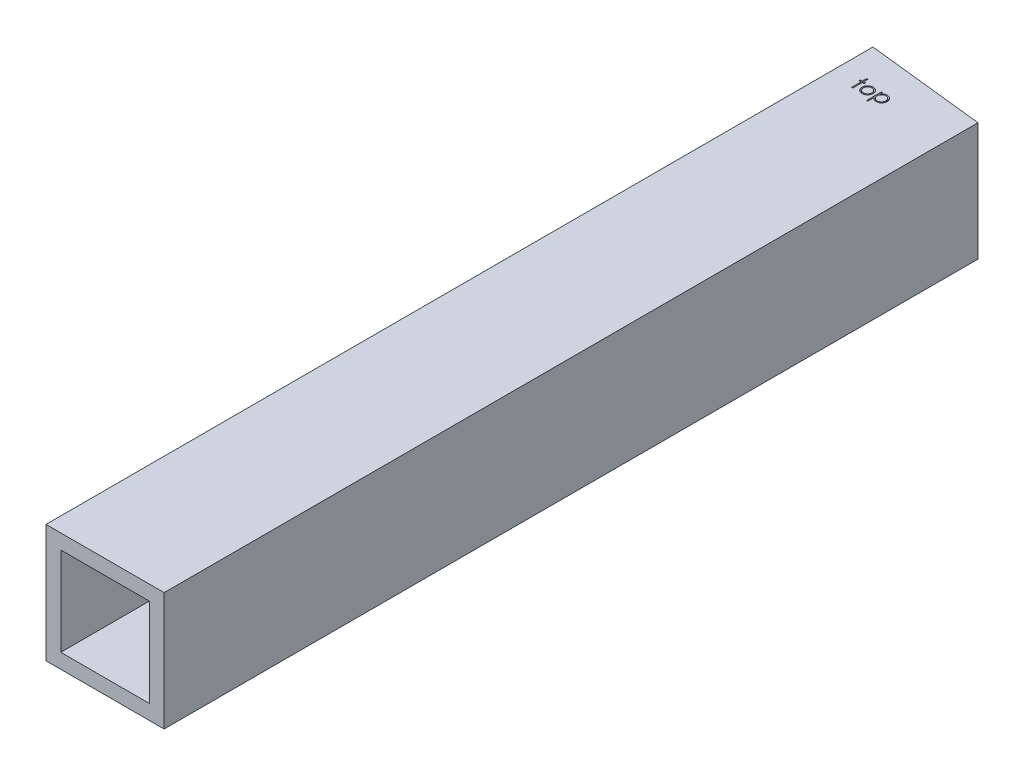
SolidWorks part; units mm, degrees
ref_plane "Front Plane" through (0, 0, 0) normal (0, 0, 1) x (1, 0, 0)
ref_plane "Top Plane" through (0, 0, 0) normal (0, 1, 0) x (1, 0, 0)
ref_plane "Right Plane" through (0, 0, 0) normal (1, 0, 0) x (0, 0, -1)
sketch "Sketch2" plane through (0, 0, 0) normal (0, 0, 1) x (1, 0, 0)
  line L1 (0, 0) -> (25.4, 0)
  line L2 (0, 0) -> (0, 25.4)
  line L3 (0, 25.4) -> (25.4, 25.4)
  line L4 (25.4, 0) -> (25.4, 25.4)
  line L5 (3.175, 22.225) -> (22.225, 22.225)
  line L6 (3.175, 22.225) -> (3.175, 3.175)
  line L7 (3.175, 3.175) -> (22.225, 3.175)
  line L8 (22.225, 22.225) -> (22.225, 3.175)
  dimension "D1" = 25.4
  dimension "D2" = 25.4
  dimension "D3" = 3.175
  dimension "D4" = 3.175
  dimension "D5" = 3.175
  dimension "D6" = 3.175
extrude "Boss-Extrude1" add sketch "Sketch2" along normal blind 177.8
sketch "Sketch3" plane through (0, 25.4, 0) normal (0, 1, 0) x (1, 0, 0)
  line L0 (0, 0) -> (25.4, -2.8042)
  line L1 (25.4, -177.8) -> (25.4, 0) construction
  line L2 (25.4, -2.8042) -> (25.4, 0)
  line L3 (25.4, 0) -> (0, 0)
  text T0 "top\r\n"
  dimension "D1" = 83.7
extrude "Cut-Extrude1" cut sketch "Sketch3" against normal through all
